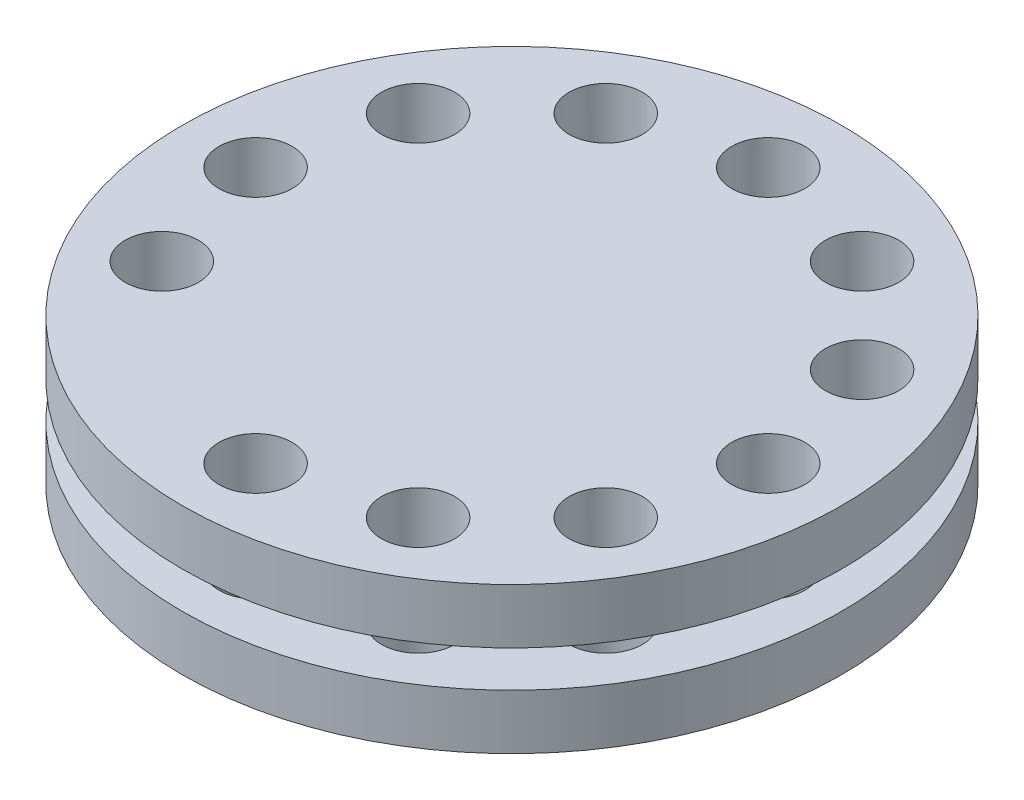
SolidWorks part; units mm, degrees
ref_plane "Front Plane" through (0, 0, 0) normal (0, 0, 1) x (1, 0, 0)
ref_plane "Top Plane" through (0, 0, 0) normal (0, 1, 0) x (1, 0, 0)
ref_plane "Right Plane" through (0, 0, 0) normal (1, 0, 0) x (0, 0, -1)
sketch "Sketch1" plane through (0, 0, 0) normal (0, 1, 0) x (1, 0, 0)
  circle A0 centre (0, 0) radius 9
  dimension "D1" = 18
extrude "Boss-Extrude1" add sketch "Sketch1" along normal blind 1.5
sketch "Sketch2" plane through (0, 1.5, 0) normal (0, 1, 0) x (1, 0, 0)
  circle A0 centre (0, 0) radius 5
  dimension "D1" = 10
extrude "Boss-Extrude2" add sketch "Sketch2" along normal blind 1
sketch "Sketch3" plane through (0, 2.5, 0) normal (0, 1, 0) x (1, 0, 0)
  circle A0 centre (0, 0) radius 9 construction
  circle A1 centre (0, 0) radius 9
extrude "Boss-Extrude3" add sketch "Sketch3" along normal blind 1.5
sketch "Sketch4" plane through (0, 0, 0) normal (0, -1, 0) x (1, 0, 0)
  line L0 (0, 9) -> (0, -9) construction
  line L5 (-9, 0) -> (9, 0) construction
  circle A20 centre (0, 7) radius 1
  circle A24 centre (0, 0) radius 9 construction
  circle A25 centre (0, 0) radius 7 construction
  circle A26 centre (3.5, 6.0622) radius 1
  circle A27 centre (0, 0) radius 7 construction
  circle A28 centre (6.0622, 3.5) radius 1
  circle A29 centre (0, 0) radius 7 construction
  circle A30 centre (7, 0) radius 1
  circle A31 centre (0, 0) radius 7 construction
  circle A32 centre (6.0622, -3.5) radius 1
  circle A33 centre (0, 0) radius 7 construction
  circle A34 centre (3.5, -6.0622) radius 1
  circle A35 centre (0, 0) radius 7 construction
  circle A36 centre (0, -7) radius 1
  circle A37 centre (0, 0) radius 7 construction
  circle A38 centre (-3.5, -6.0622) radius 1
  circle A39 centre (0, 0) radius 7 construction
  circle A40 centre (-6.0622, -3.5) radius 1
  circle A41 centre (0, 0) radius 7 construction
  circle A42 centre (-7, 0) radius 1
  circle A43 centre (0, 0) radius 7 construction
  circle A44 centre (-6.0622, 3.5) radius 1
  circle A45 centre (0, 0) radius 7 construction
  circle A46 centre (-3.5, 6.0622) radius 1
  circle A47 centre (0, 0) radius 7 construction
  point P0 (0, 0)
  point P49 (0, 0)
  dimension "D3" = 2
  dimension "D2" = 7
  dimension "D1" = 12
extrude "Cut-Extrude1" cut sketch "Sketch4" against normal through all
sketch "Sketch6" plane through (0, 4, 0) normal (0, 1, 0) x (1, 0, 0)
  circle A0 centre (-3.5, -6.0622) radius 1
  circle A1 centre (-3.5, -6.0622) radius 1 construction
extrude "Boss-Extrude4" add sketch "Sketch6" against normal up to surface (4 mm away) up to face at (6.0622, 0, 2.5)
